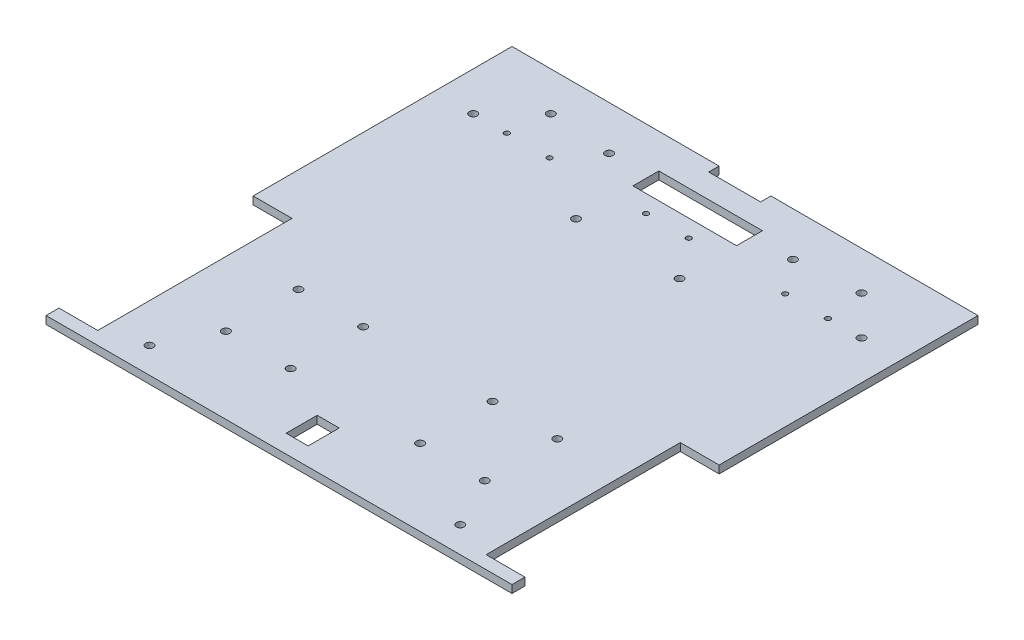
SolidWorks part; units mm, degrees
ref_plane "Front Plane" through (0, 0, 0) normal (0, 0, 1) x (1, 0, 0)
ref_plane "Top Plane" through (0, 0, 0) normal (0, 1, 0) x (1, 0, 0)
ref_plane "Right Plane" through (0, 0, 0) normal (1, 0, 0) x (0, 0, -1)
sketch "Sketch1" plane through (0, 0, 0) normal (0, 1, 0) x (1, 0, 0)
  line L1 (-90, 90) -> (90, 90)
  line L6 (-90, 90) -> (-90, -90)
  line L7 (-90, -90) -> (90, -90)
  line L8 (90, 90) -> (90, -90)
  line L9 (-90, 90) -> (90, -90) construction
  line L10 (-90, -90) -> (90, 90) construction
  point P0 (0, 0)
  dimension "D1" = 180
  dimension "D2" = 180
extrude "Boss-Extrude1" add sketch "Sketch1" along normal blind 3
sketch "Sketch2" plane through (0, 3, 0) normal (0, 1, 0) x (1, 0, 0)
  line L0 (-90, 90) -> (-90, -90) construction
  line L5 (-90, -10) -> (-75, -10)
  line L6 (-90, -10) -> (-90, -85)
  line L7 (-90, -85) -> (-75, -85)
  line L8 (-75, -10) -> (-75, -85)
  line L14 (0, 0) -> (0, -94.1115) construction
  line L15 (90, -85) -> (75, -85)
  line L16 (90, -10) -> (90, -85)
  line L17 (75, -10) -> (75, -85)
  line L18 (90, -10) -> (75, -10)
  line L19 (-90, -90) -> (90, -90) construction
  dimension "D1" = 75
  dimension "D2" = 15
  dimension "D3" = 5
extrude "Cut-Extrude1" cut sketch "Sketch2" against normal blind 3
sketch "Sketch3" plane through (0, 3, 0) normal (0, 1, 0) x (1, 0, 0)
  line L0 (-75, -85) -> (-75, -10) construction
  line L1 (-75, -10) -> (-90, -10) construction
  line L2 (0, 0) -> (0, -66.2917) construction
  line L3 (-90, -90) -> (90, -90) construction
  line L4 (-90, 90) -> (-90, -10) construction
  line L5 (90, 90) -> (-90, 90) construction
  line L6 (90, -10) -> (90, 90) construction
  line L7 (-20, 76.7275) -> (20, 76.7275)
  line L8 (-20, 76.7275) -> (-20, 66.7275)
  line L9 (-20, 66.7275) -> (20, 66.7275)
  line L10 (20, 76.7275) -> (20, 66.7275)
  circle A0 centre (-50, -32.5) radius 1.5
  circle A1 centre (-50, -60.5) radius 1.5
  circle A2 centre (-25, -32.5) radius 1.5
  circle A3 centre (-25, -60.5) radius 1.5
  circle A4 centre (25, -60.5) radius 1.5
  circle A5 centre (50, -60.5) radius 1.5
  circle A6 centre (25, -32.5) radius 1.5
  circle A7 centre (50, -32.5) radius 1.5
  circle A8 centre (-60, -80) radius 1.5
  circle A9 centre (60, -80) radius 1.5
  circle A10 centre (-62, 60) radius 1
  circle A11 centre (-45.5, 60) radius 1
  circle A12 centre (45.5, 60) radius 1
  circle A13 centre (62, 60) radius 1
  circle A14 centre (-60, 75) radius 1.5
  circle A15 centre (60, 75) radius 1.5
  circle A16 centre (-8.25, 60) radius 1
  circle A17 centre (8.25, 60) radius 1
  circle A18 centre (-20, 44.7275) radius 1.5
  circle A19 centre (20, 44.7275) radius 1.5
  dimension "D1" = 3
  dimension "D2" = 3
  dimension "D3" = 3
  dimension "D4" = 3
  dimension "D5" = 25
  dimension "D11" = 3
  dimension "D15" = 2
  dimension "D16" = 2
  dimension "D19" = 3
  dimension "D24" = 3
  dimension "D6" = 25
  dimension "D7" = 28
  dimension "D8" = 22.5
  dimension "D9" = 10
  dimension "D10" = 15
  dimension "D12" = 28
  dimension "D13" = 16.5
  dimension "D14" = 30
  dimension "D17" = 30
  dimension "D18" = 15
  dimension "D20" = 8.25
  dimension "D21" = 40
  dimension "D22" = 10
  dimension "D23" = 70
  dimension "D25" = 22
  dimension "D26" = 20
extrude "Cut-Extrude2" cut sketch "Sketch3" against normal blind 3
sketch "Sketch5" plane through (0, 3, 0) normal (0, 1, 0) x (1, 0, 0)
  line L0 (-90, 90) -> (-90, -10) construction
  line L1 (0, 0) -> (0, -39.8124) construction
  line L2 (90, 90) -> (-90, 90) construction
  circle A0 centre (-75, 60) radius 1.5
  circle A1 centre (75, 60) radius 1.5
  circle A2 centre (-35.5, 73) radius 1.5
  circle A3 centre (35.5, 73) radius 1.5
  dimension "D1" = 3
  dimension "D4" = 3
  dimension "D2" = 15
  dimension "D3" = 30
  dimension "D5" = 17
  dimension "D6" = 54.5
extrude "Cut-Extrude3" cut sketch "Sketch5" against normal blind 3
sketch "Sketch7" plane through (0, 3, 0) normal (0, 1, 0) x (1, 0, 0)
  line L0 (90, 90) -> (-90, 90) construction
  line L1 (-10, 90) -> (10, 90)
  line L2 (-10, 90) -> (-10, 86)
  line L3 (-10, 86) -> (10, 86)
  line L4 (10, 90) -> (10, 86)
  line L5 (90, -10) -> (90, 90) construction
  point P6 (10, 88)
  dimension "D1" = 4
  dimension "D2" = 20
  dimension "D3" = 80
extrude "Cut-Extrude4" cut sketch "Sketch7" against normal blind 3
sketch "Sketch8" plane through (0, 3, 0) normal (0, 1, 0) x (1, 0, 0)
  line L0 (-90, -90) -> (90, -90) construction
  line L1 (-4.25, -71) -> (4.25, -71)
  line L2 (-4.25, -71) -> (-4.25, -83)
  line L3 (-4.25, -83) -> (4.25, -83)
  line L4 (4.25, -71) -> (4.25, -83)
  line L5 (-4.25, -71) -> (4.25, -83) construction
  line L6 (-4.25, -83) -> (4.25, -71) construction
  line L7 (-90, -85) -> (-90, -90) construction
  point P0 (0, -77)
  dimension "D1" = 7
  dimension "D2" = 12
  dimension "D3" = 8.5
  dimension "D4" = 90
extrude "Cut-Extrude5" cut sketch "Sketch8" against normal blind 3
